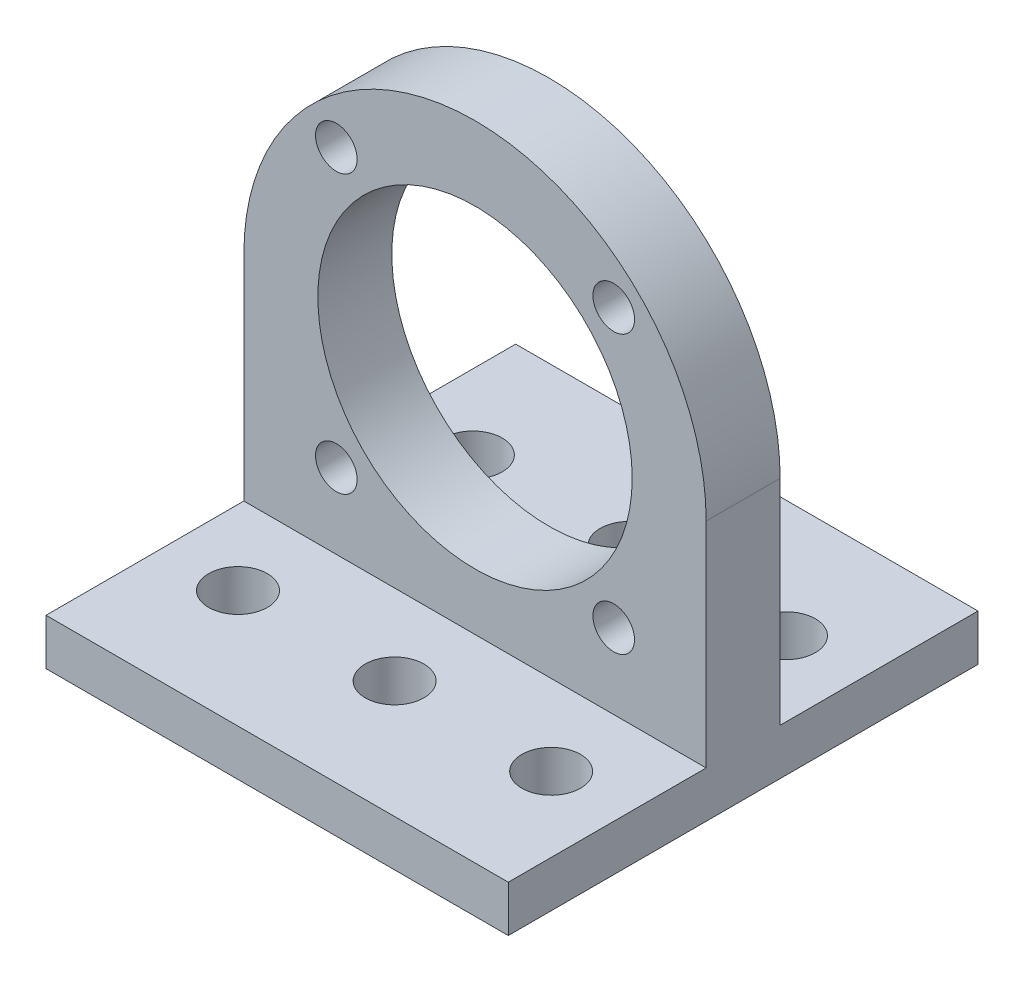
SolidWorks part; units mm, degrees
ref_plane "Front Plane" through (0, 0, 0) normal (0, 0, 1) x (1, 0, 0)
ref_plane "Top Plane" through (0, 0, 0) normal (0, 1, 0) x (1, 0, 0)
ref_plane "Right Plane" through (0, 0, 0) normal (1, 0, 0) x (0, 0, -1)
ref_plane "Plane1"
sketch "Sketch1" plane through (0, 0, 0) normal (0, 0, 1) x (1, 0, 0)
  line L0 (-25, 0) -> (-25, -23.1305)
  line L1 (-25, -23.1305) -> (25, -23.1305)
  line L2 (25, -23.1305) -> (25, 0)
  arc A0 (25, 0) -> (-25, 0) centre (0, 0) ccw
  circle A1 centre (0, 0) radius 17
  dimension "D1" = 34
  dimension "D2" = 50
  dimension "D3" = 50
  dimension "D4" = 23.1305
extrude "Extrusion1" add sketch "Sketch1" along normal blind 8 contours L2 A0 L0 L1 A1
sketch "Sketch2" plane through (0, -23.1305, 0) normal (0, -1, 0) x (1, 0, 0)
  line L0 (-25, -21.4) -> (25, -21.4)
  line L1 (25, -21.4) -> (25, 29.4)
  line L2 (25, 29.4) -> (-25, 29.4)
  line L3 (-25, 29.4) -> (-25, -21.4)
  dimension "D1" = 50.8
  dimension "D2" = 50
extrude "Extrusion2" add sketch "Sketch2" along normal blind 5
hole_wizard "Hole2" positions "Sketch4" profile "Sketch3" legacy end condition through all
sketch "Sketch4" plane through (0, -28.1305, 0) normal (0, -1, 0) x (-1, 0, 0)
  point P1 (16.9333, -16.7)
  point P2 (0, -16.7)
  point P3 (16.9333, 8.7)
  point P4 (0, 8.7)
  point P5 (-16.9333, -16.7)
  point P6 (-16.9333, 8.7)
sketch "Sketch3" plane through (-16.9333, -28.1305, 16.7) normal (1, 0, 0) x (0, 0, -1)
  line L0 (0, 0) -> (0, 53.1305)
  line L1 (0, 53.1305) -> (3.175, 53.1305)
  line L2 (3.175, 53.1305) -> (3.175, 0)
  line L3 (3.175, 0) -> (0, 0)
  line L4 (0, 110) -> (0, -10) construction
  dimension "Diameter" = 6.35
  dimension "Depth" = 53.1305
hole_wizard "Hole3" positions "Sketch6" profile "Sketch5" legacy end condition through all
sketch "Sketch6" plane through (0, 0, 0) normal (0, 0, -1) x (-1, 0, 0)
  point P1 (-15, 15)
  point P2 (15, 15)
  point P3 (-15, -15)
  point P4 (15, -15)
sketch "Sketch5" plane through (15, 15, 0) normal (1, 0, 0) x (0, 1, 0)
  line L0 (0, 0) -> (0, 29.4)
  line L1 (0, 29.4) -> (2.25, 29.4)
  line L2 (2.25, 29.4) -> (2.25, 0)
  line L3 (2.25, 0) -> (0, 0)
  line L4 (0, 110) -> (0, -10) construction
  dimension "Diameter" = 4.5
  dimension "Depth" = 29.4
